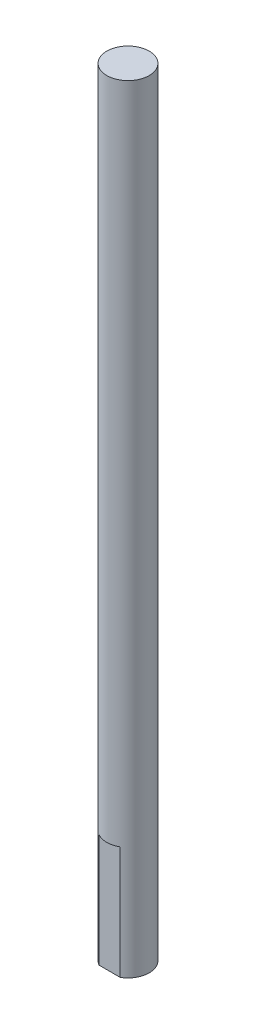
SolidWorks part; units mm, degrees
ref_plane "Front Plane" through (0, 0, 0) normal (0, 0, 1) x (1, 0, 0)
ref_plane "Top Plane" through (0, 0, 0) normal (0, 1, 0) x (1, 0, 0)
ref_plane "Right Plane" through (0, 0, 0) normal (1, 0, 0) x (0, 0, -1)
sketch "Sketch1" plane through (0, 0, 0) normal (0, 1, 0) x (1, 0, 0)
  circle A0 centre (0, 0) radius 1.5
  dimension "D1" = 3
extrude "Boss-Extrude1" add sketch "Sketch1" along normal blind 55
sketch "Sketch2" plane through (0, 0, 0) normal (0, -1, 0) x (1, 0, 0)
  line L0 (-0.7483, 1.3) -> (0.7483, 1.3)
  arc A0 (0.7483, 1.3) -> (-0.7483, 1.3) centre (0, 0) ccw
  circle A1 centre (0, 0) radius 1.5 construction
  point P1 (0, -1.5)
  dimension "D1" = 2.8
extrude "Cut-Extrude1" cut sketch "Sketch2" against normal blind 8
